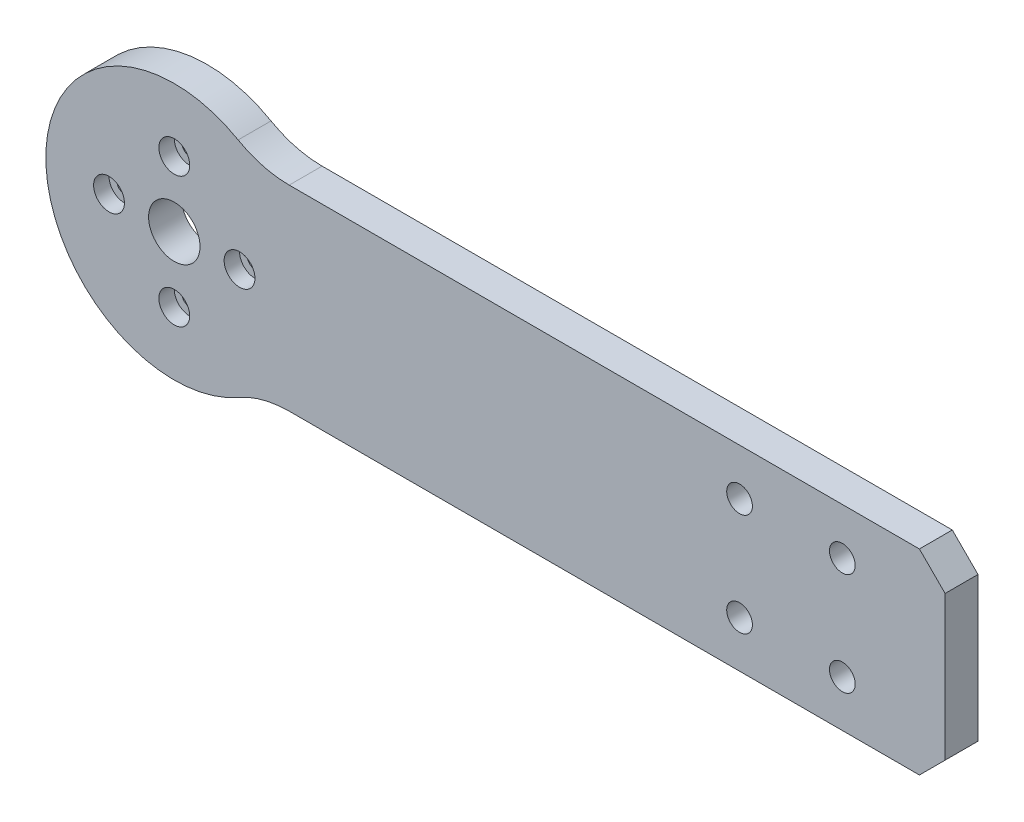
SolidWorks part; units mm, degrees
material "7075-T6, Plate (SS)"
ref_plane "Front Plane" through (0, 0, 0) normal (0, 0, 1) x (1, 0, 0)
ref_plane "Top Plane" through (0, 0, 0) normal (0, 1, 0) x (1, 0, 0)
ref_plane "Right Plane" through (0, 0, 0) normal (1, 0, 0) x (0, 0, -1)
sketch "Sketch1" plane through (0, 0, 0) normal (0, 0, 1) x (1, 0, 0)
  line L0 (0, 0) -> (150, 0) construction
  line L2 (150, 19.05) -> (16.1894, 19.05)
  line L3 (150, 19.05) -> (150, -19.05)
  line L4 (150, -19.05) -> (16.1894, -19.05)
  arc A0 (16.1894, 19.05) -> (16.1894, -19.05) centre (0, 0) ccw
  circle A1 centre (0, 0) radius 5
  circle A2 centre (0, 0) radius 12.7 construction
  circle A3 centre (130, 10) radius 2.5
  circle A4 centre (110, 10) radius 2.5
  circle A5 centre (110, -10) radius 2.5
  circle A6 centre (130, -10) radius 2.5
  circle A7 centre (0, 12.7) radius 1.5
  circle A8 centre (0, -12.7) radius 1.5
  circle A9 centre (12.7, 0) radius 1.5
  circle A10 centre (-12.7, 0) radius 1.5
  dimension "D2" = 50
  dimension "D3" = 10
  dimension "D5" = 5
  dimension "D10" = 25.4
  dimension "D11" = 3
  dimension "D1" = 150
  dimension "D4" = 38.1
  dimension "D6" = 20
  dimension "D7" = 20
  dimension "D8" = 10
  dimension "D9" = 10
extrude "Boss-Extrude1" add sketch "Sketch1" along normal blind 6.4
sketch "Sketch2" plane through (0, 0, 6.4) normal (0, 0, 1) x (1, 0, 0)
  line L2 (0, 12.7) -> (0, 0) construction
  line L3 (0, 0) -> (12.7, 0) construction
  circle A0 centre (0, 12.7) radius 3
  circle A1 centre (12.7, 0) radius 3
  circle A2 centre (0, -12.7) radius 3
  circle A3 centre (-12.7, 0) radius 3
  point P12 (0, 0)
  dimension "D1" = 6
  dimension "D2" = 4
extrude "Cut-Extrude1" cut sketch "Sketch2" against normal blind 3
chamfer "Chamfer1" distance 5 angle 45 2 edges at (150, -19.05, 3.2) (150, 19.05, 3.2)
fillet "Fillet1" radius 20 2 edges at (16.1894, -19.05, 3.2) (16.1894, 19.05, 3.2)
